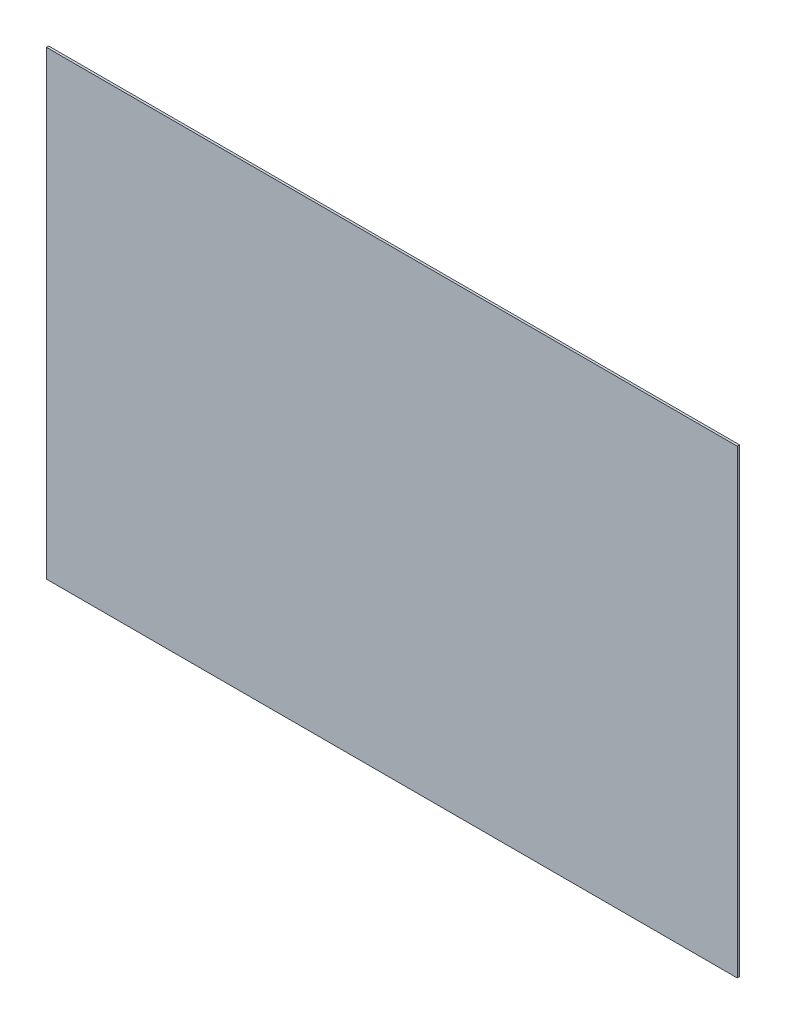
SolidWorks part; units mm, degrees
material "PC haute viscosité"
ref_plane "Plan de face" through (0, 0, 0) normal (0, 0, 1) x (1, 0, 0)
ref_plane "Plan de dessus" through (0, 0, 0) normal (0, 1, 0) x (1, 0, 0)
ref_plane "Plan de droite" through (0, 0, 0) normal (1, 0, 0) x (0, 0, -1)
sketch "Esquisse1" plane through (0, 0, 0) normal (0, 0, 1) x (1, 0, 0)
  line L1 (0, 0) -> (-600, 0)
  line L2 (0, 0) -> (0, 400)
  line L3 (0, 400) -> (-600, 400)
  line L4 (-600, 0) -> (-600, 400)
  dimension "D1" = 600
  dimension "D2" = 400
extrude "Boss.-Extru.1" add sketch "Esquisse1" along normal blind 2
